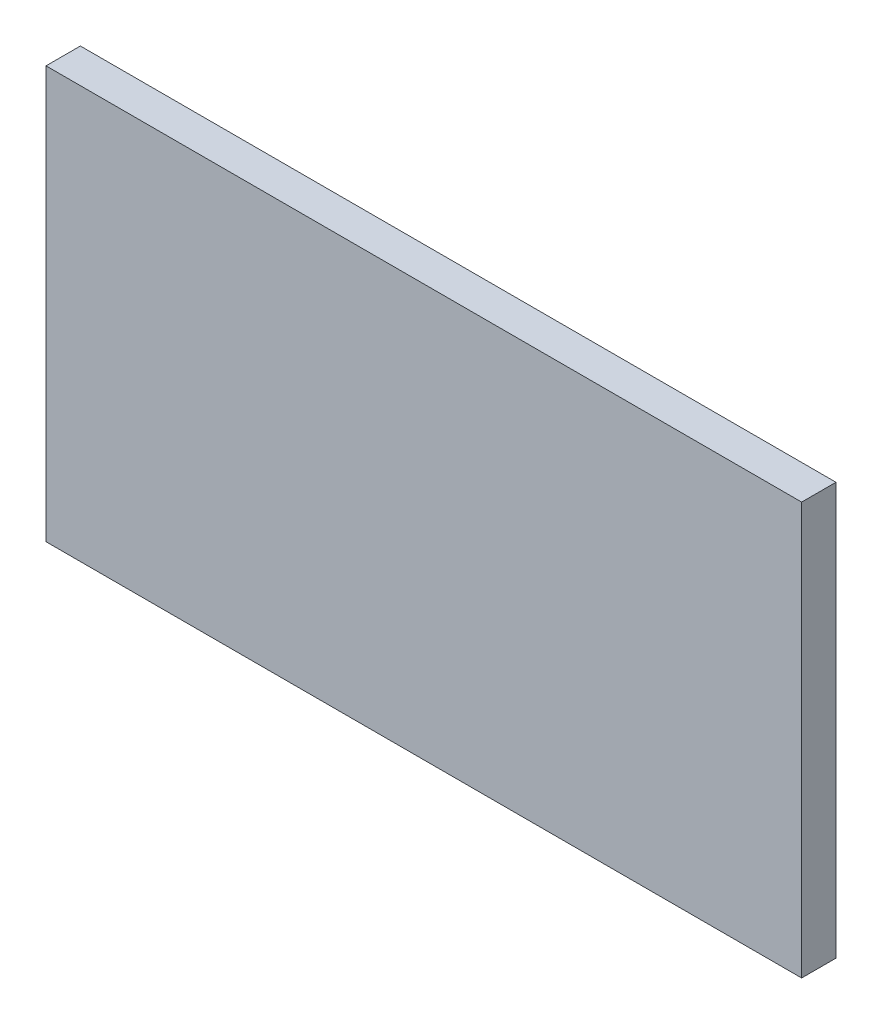
SolidWorks part; units mm, degrees
ref_plane "정면" through (0, 0, 0) normal (0, 0, 1) x (1, 0, 0)
ref_plane "윗면" through (0, 0, 0) normal (0, 1, 0) x (1, 0, 0)
ref_plane "우측면" through (0, 0, 0) normal (1, 0, 0) x (0, 0, -1)
sketch "스케치1" plane through (0, 0, 0) normal (0, 0, 1) x (1, 0, 0)
  line L1 (-55, 30) -> (55, 30)
  line L2 (-55, 30) -> (-55, -30)
  line L3 (-55, -30) -> (55, -30)
  line L4 (55, 30) -> (55, -30)
  line L5 (-55, 30) -> (55, -30) construction
  line L6 (-55, -30) -> (55, 30) construction
  point P0 (0, 0)
  dimension "D1" = 60
  dimension "D2" = 110
extrude "보스-돌출1" add sketch "스케치1" along normal blind 5
